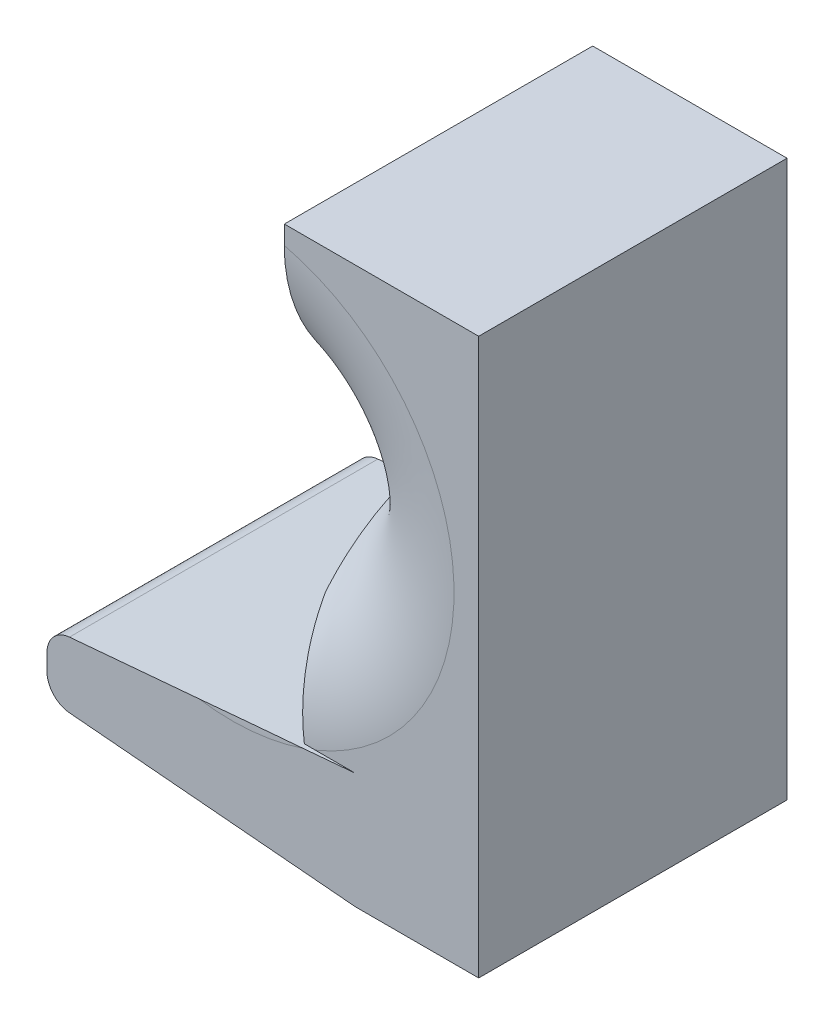
SolidWorks part; units mm, degrees
ref_plane "Front Plane" through (0, 0, 0) normal (0, 0, 1) x (1, 0, 0)
ref_plane "Top Plane" through (0, 0, 0) normal (0, 1, 0) x (1, 0, 0)
ref_plane "Right Plane" through (0, 0, 0) normal (1, 0, 0) x (0, 0, -1)
sketch "finger" plane through (0, 0, 0) normal (0, 0, 1) x (1, 0, 0)
  line L0 (0, 0) -> (5.0161, 13.7815) construction
  line L1 (5.0161, 13.7815) -> (5.0161, 28.518) construction
  line L2 (0, 0) -> (-4.105, -46.9208)
  line L3 (-4.105, -46.9208) -> (14.5481, -62.5726)
  line L4 (14.5481, -62.5726) -> (32.0314, -57.888)
  line L5 (30.802, -53.2999) -> (13.3188, -57.9845)
  line L6 (12.0894, -53.3964) -> (29.5726, -48.7117)
  line L7 (12.0894, -53.3964) -> (13.3188, -57.9845)
  line L8 (13.3188, -57.9845) -> (14.5481, -62.5726)
  line L9 (30.802, -53.2999) -> (35.3902, -52.0705) construction
  circle A0 centre (30.802, -53.2999) radius 4.75
  dimension "D3" = 15
  dimension "D4" = 55
  dimension "D5" = 20
  dimension "D6" = 55
  dimension "D7" = 47.1
  dimension "D8" = 24.35
  dimension "D2" = 9.5
  dimension "D1" = 22.85
ref_plane "est_lift_plane" through (30.802, 0, 0) normal (1, 0, 0) x (0, 0, -1)
sketch "master_derived" plane through (0, 0, 0) normal (0, 0, 1) x (1, 0, 0)
  line L0 (0, 1.5) -> (0, 4.5)
  line L1 (0, 4.5) -> (0, 5.5)
  line L2 (0, 1.5) -> (0, 1.6)
  line L3 (0, 1.6) -> (0, 1.65)
  line L4 (4.2426, -3.5) -> (10, -3.5)
  line L5 (0, 0) -> (10, 0)
  line L6 (0, -4.5) -> (10, -4.5)
  line L7 (4.2426, -3.5) -> (4.2426, -4.5)
  line L8 (4.2426, -3.5) -> (4.2426, 12.8193)
  line L10 (4.2426, 12.8193) -> (19.2426, 12.8193)
  line L11 (19.2426, 12.8193) -> (19.2426, -21.9021)
  line L12 (-23.405, -20.4436) -> (10, -21.9021)
  line L13 (-23.405, -20.4436) -> (-23.405, -15.4436)
  line L14 (-23.405, -15.4436) -> (10, -13.9851)
  line L15 (10, -13.9851) -> (10, -4.5)
  line L16 (-19.405, -15.269) -> (-19.405, -20.6183)
  line L17 (-23.405, -17.9436) -> (-19.405, -17.9436)
  line L18 (0, 1.5) -> (0, 1.65)
  line L19 (10, -21.9021) -> (19.2426, -21.9021)
  line L20 (0, 12.8193) -> (0, 10.8193) construction
  circle A0 centre (0, 0) radius 5.5
  circle A1 centre (0, 0) radius 4.5
  circle A2 centre (0, 0) radius 1.5
  circle A3 centre (0, 0) radius 1.6
  circle A4 centre (0, 0) radius 1.65
sketch "Sketch2" plane through (0, 0, 0) normal (0, 0, 1) x (1, 0, 0)
  line L0 (25.552, -42.5499) -> (25.552, -39.5499) construction
  line L1 (25.552, -39.5499) -> (25.552, -38.5499) construction
  line L2 (25.552, -42.5499) -> (25.552, -42.4499) construction
  line L3 (25.552, -42.4499) -> (25.552, -42.3999) construction
  line L4 (29.7947, -47.5499) -> (35.552, -47.5499) construction
  line L5 (25.552, -44.0499) -> (35.552, -44.0499) construction
  line L6 (25.552, -48.5499) -> (35.552, -48.5499) construction
  line L7 (29.7947, -47.5499) -> (29.7947, -48.5499)
  line L8 (29.7947, -47.5499) -> (29.7947, -25.0499)
  line L9 (29.7947, -25.0499) -> (45.552, -25.0499)
  line L10 (45.552, -25.0499) -> (45.552, -70.1102)
  line L12 (10.5481, -67.9226) -> (10.5481, -62.9226)
  line L13 (10.5481, -62.9226) -> (35.552, -60.735)
  line L14 (35.552, -60.735) -> (35.552, -48.5499)
  line L15 (14.5481, -62.5726) -> (14.5481, -68.2726)
  line L16 (10.5481, -65.4226) -> (14.5481, -65.4226)
  line L17 (25.552, -42.5499) -> (25.552, -42.3999) construction
  line L23 (29.7947, -48.5499) -> (29.7947, -61.0499) construction
  line L24 (25.552, -44.0499) -> (25.552, -61.0499) construction
  line L25 (25.552, -44.0499) -> (25.552, -27.0499) construction
  line L26 (25.552, -27.0499) -> (25.552, -25.0499) construction
  line L28 (29.7947, -48.5499) -> (35.552, -48.5499)
  line L30 (10.5481, -67.9226) -> (35.552, -70.1102)
  line L34 (35.552, -70.1102) -> (45.552, -70.1102)
  line L41 (4.2426, -3.5) -> (4.2426, -4.5) construction
  line L42 (0, 0) -> (10, 0) construction
  line L43 (0, 12.8193) -> (0, 10.8193) construction
  line L44 (-23.405, -20.4436) -> (-23.405, -15.4436) construction
  line L45 (-23.405, -17.9436) -> (-19.405, -17.9436) construction
  circle A0 centre (25.552, -44.0499) radius 5.5 construction
  circle A1 centre (25.552, -44.0499) radius 4.5 construction
  circle A2 centre (25.552, -44.0499) radius 1.5 construction
  circle A3 centre (25.552, -44.0499) radius 1.6 construction
  circle A4 centre (25.552, -44.0499) radius 1.65 construction
  circle A9 centre (0, 0) radius 5.5 construction
  circle A12 centre (30.802, -53.2999) radius 4.75 construction
  circle A14 centre (0, 0) radius 4.5 construction
  circle A15 centre (0, 0) radius 1.5 construction
  circle A16 centre (0, 0) radius 1.6 construction
  circle A17 centre (0, 0) radius 1.65 construction
  dimension "D2" = 5
  dimension "D1" = 12.5
  dimension "D3" = 10
extrude "Boss-Extrude1" add sketch "Sketch2" along normal mid plane 25
sketch "Sketch4" plane through (35.552, 0, 0) normal (-1, 0, 0) x (0, 0, 1)
  line L0 (0, -37.9263) -> (0, 37.9263) construction
  line L1 (-12.5, -61.0499) -> (-12.5, -48.5499)
  line L2 (-12.5, -48.5499) -> (12.5, -48.5499)
  line L3 (12.5, -48.5499) -> (12.5, -61.0499)
  circle A0 centre (0, -61.0499) radius 12.5 construction
  arc A1 (-12.5, -61.0499) -> (12.5, -61.0499) centre (0, -61.0499) cw
  line M4 (-12.5, -48.5499) -> (-12.5, -60.735)
  line M6 (12.5, -60.735) -> (12.5, -48.5499)
  line M7 (12.5, -48.5499) -> (-12.5, -48.5499)
extrude "Boss-Extrude2" add sketch "Sketch4" along normal up to surface (5.7574 mm away) contours A1 L2 M4 | A1 M7 M6
ref_plane "roller_plane" through (25.552, 0, 0) normal (-1, 0, 0) x (0, 0, 1)
sketch "Sketch3" plane through (25.552, 0, 0) normal (-1, 0, 0) x (0, 0, 1)
  line L0 (0, -37.9263) -> (0, 37.9263) construction
  line L1 (0, 0) -> (0, -46.9208) construction
  line L2 (-12.5, -44.0499) -> (12.5, -44.0499)
  line L3 (-12.5, -60.735) -> (-12.5, -25.0499) construction
  line L4 (12.5, -25.0499) -> (12.5, -60.735) construction
  line L5 (-12.5, -44.0499) -> (-12.5, -26.0499)
  line L6 (12.5, -44.0499) -> (12.5, -26.0499)
  circle A0 centre (0, -26.0499) radius 12.5 construction
  arc A1 (-12.5, -26.0499) -> (12.5, -26.0499) centre (0, -26.0499) ccw
revolve "Cut-Revolve1" cut sketch "Sketch3" angle 360 about L2
fillet "Fillet2" radius 2 2 edges at (10.5481, -62.9226, 0) (10.5481, -67.9226, 0)
equation "\"depth\"= 9"
equation "\"width\"=25"
equation "\"distal\"= 22.85"
equation "\"proximal\"= 47.1"
equation "\"medial\"= 24.35"
equation "\"D7@finger\" = \"proximal\""
equation "\"D8@finger\" = \"medial\""
equation "\"D1@Boss-Extrude1\"=\"width\""
equation "\"D1@finger\"=\"distal\""
equation "\"D1@Sketch2\"=\"width\"/2"
